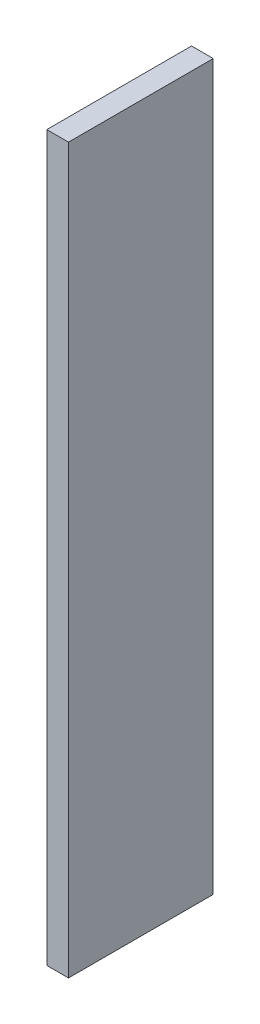
SolidWorks part; units mm, degrees
ref_plane "前视基准面" through (0, 0, 0) normal (0, 0, 1) x (1, 0, 0)
ref_plane "上视基准面" through (0, 0, 0) normal (0, 1, 0) x (1, 0, 0)
ref_plane "右视基准面" through (0, 0, 0) normal (1, 0, 0) x (0, 0, -1)
sketch "草图3" plane through (0, 0, 0) normal (0, 0, 1) x (1, 0, 0)
  line L1 (-15, 500) -> (15, 500)
  line L2 (-15, 500) -> (-15, -500)
  line L3 (-15, -500) -> (15, -500)
  line L4 (15, 500) -> (15, -500)
  line L5 (-15, 500) -> (15, -500) construction
  line L6 (-15, -500) -> (15, 500) construction
  point P0 (0, 0)
  dimension "D1" = 30
  dimension "D2" = 1000
extrude "凸台-拉伸1" add sketch "草图3" along normal mid plane 200
sketch "草图6" plane through (-15, 0, 0) normal (-1, 0, 0) x (0, 0, 1)
  circle A0 centre (0, 375) radius 50
extrude "凸台-拉伸2" add sketch "草图6" along normal blind 20
pattern_linear "阵列(线性)1" count 4 spacing 250 along (0, -1, 0) of "凸台-拉伸2"
